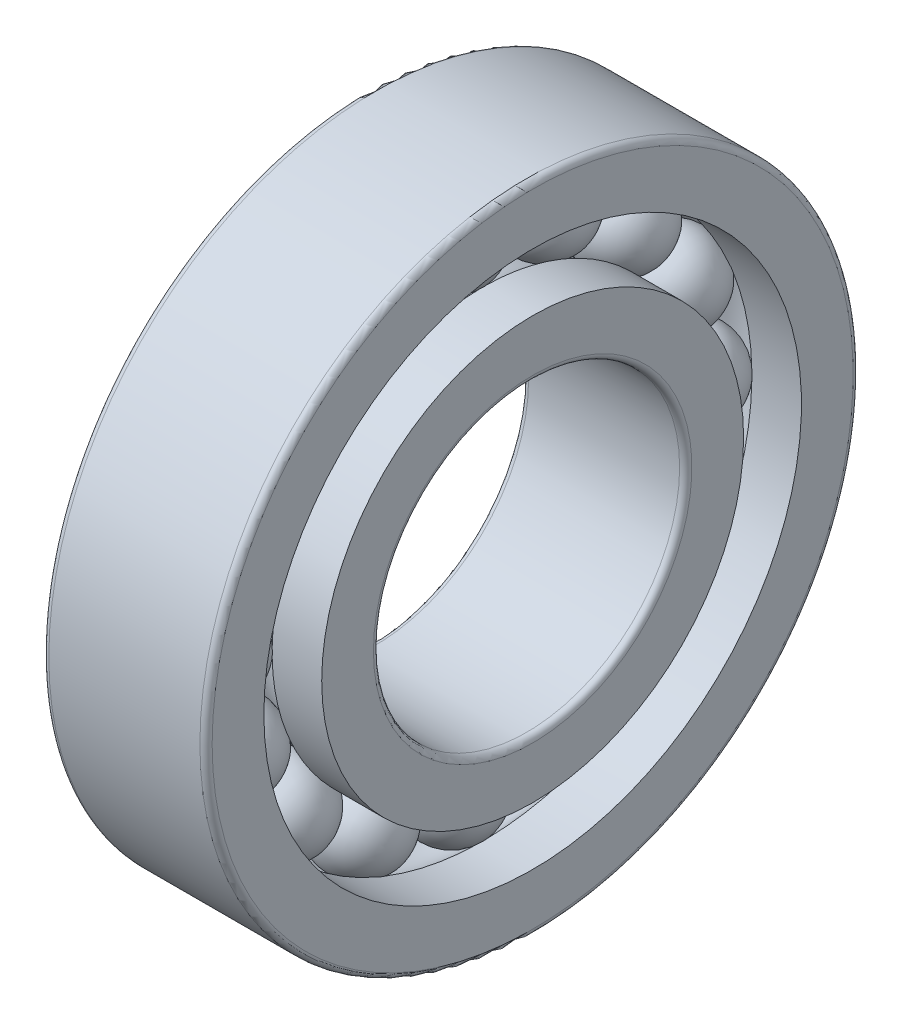
SolidWorks part; units mm, degrees
ref_plane "Front" through (0, 0, 0) normal (0, 0, 1) x (1, 0, 0)
ref_plane "Top" through (0, 0, 0) normal (0, 1, 0) x (1, 0, 0)
ref_plane "Right" through (0, 0, 0) normal (1, 0, 0) x (0, 0, -1)
sketch "Sketch1" plane through (0, 0, 0) normal (0, 0, 1) x (1, 0, 0)
  line L0 (-9.6833, 0) -> (9.8371, 0) construction
  line L1 (-2.125, 11.75) -> (2.125, 11.75)
  line L2 (-4.5966, 11.75) -> (4.6657, 11.75) construction
  arc A0 (2.125, 11.75) -> (-2.125, 11.75) centre (0, 11.75) ccw
  dimension "dia" = 4.25
  dimension "d0" = 23.5
revolve "Revolve1" add sketch "Sketch1" angle 360 about L2
sketch "Sketch2" plane through (0, 0, 0) normal (0, 0, 1) x (1, 0, 0)
  line L0 (-4, 10.3333) -> (-4, 7.5)
  line L1 (-4, 7.5) -> (4, 7.5)
  line L2 (4, 7.5) -> (4, 10.3333)
  line L3 (4, 10.3333) -> (1.5704, 10.3333)
  line L4 (-6.9714, 0) -> (8.1665, 0) construction
  line L5 (-6.7058, 11.75) -> (6.7058, 11.75) construction
  line L6 (-1.5704, 10.3333) -> (-4, 10.3333)
  arc A0 (-1.5704, 10.3333) -> (1.5704, 10.3333) centre (0, 11.75) ccw
  dimension "B" = 8
  dimension "D5" = 4.23
  dimension "d" = 15
  dimension "D3" = 11.75
  dimension "D4" = 2.8333
  dimension "B/2" = 4
revolve "Revolve2" add sketch "Sketch2" angle 360 about L4
sketch "Sketch3" plane through (0, 0, 0) normal (0, 0, 1) x (1, 0, 0)
  line L0 (-8.7107, 0) -> (9.1288, 0) construction
  line L1 (-4, 16) -> (4, 16)
  line L2 (-4, 16) -> (-4, 13.1667)
  line L3 (-4, 13.1667) -> (-1.5704, 13.1667)
  line L4 (4, 16) -> (4, 13.1667)
  line L5 (-7.2948, 11.75) -> (7.2948, 11.75) construction
  line L6 (1.5704, 13.1667) -> (4, 13.1667)
  arc A0 (1.5704, 13.1667) -> (-1.5704, 13.1667) centre (0, 11.75) ccw
  dimension "D1" = 4.23
  dimension "DD" = 32
  dimension "B" = 8
  dimension "D4" = 11.75
  dimension "D5" = 2.8333
  dimension "B/2" = 4
revolve "Revolve3" add sketch "Sketch3" angle 360 about L0
pattern_circular "Circular-Pattern1" count 16 over 360 about axis through (0, 0, 0) along (1, 0, 0) of "Revolve1"
fillet "Fillet1" radius 0.3 4 edges at (-4, 0, 7.5) (-4, 0, 16) (4, 0, 16) (4, 0, 7.5)
equation "\"d0@Sketch1\" = ( \"DD@Sketch3\" + \"d@Sketch2\" )  / 2"
equation "\"dia@Sketch1\" =  ( \"DD@Sketch3\" - \"d@Sketch2\" )  / 4"
equation "\"D3@Sketch2\" = ( \"DD@Sketch3\" + \"d@Sketch2\" )  / 2 / 2"
equation "\"D4@Sketch2\" = ( \"DD@Sketch3\" - \"d@Sketch2\" )  / 6"
equation "\"D5@Sketch2\" = \"dia@Sketch1\" - 0.02"
equation "\"B/2@Sketch2\" = \"B@Sketch2\" / 2"
equation "\"D4@Sketch3\" = ( \"DD@Sketch3\" + \"d@Sketch2\" )  / 2 / 2"
equation "\"D5@Sketch3\" = ( \"DD@Sketch3\" - \"d@Sketch2\" )  / 6"
equation "\"B@Sketch3\" = \"B@Sketch2\""
equation "\"B/2@Sketch3\" = \"B@Sketch3\" / 2"
equation "\"D1@Sketch3\" = \"dia@Sketch1\" - 0.02"
equation "\"m@Circular-Pattern1\" = int( 3.14159265 / atn(( \"dia@Sketch1\" / 2) / sqr(( \"DD@Sketch3\" + \"d@Sketch2\" )  / 2 * ( \"DD@Sketch3\" + \"d@Sketch2\" )  / 2/4 - ( \"dia@Sketch1\" / 2) *  ( \"dia@Sketch1\" / 2))))-1"
